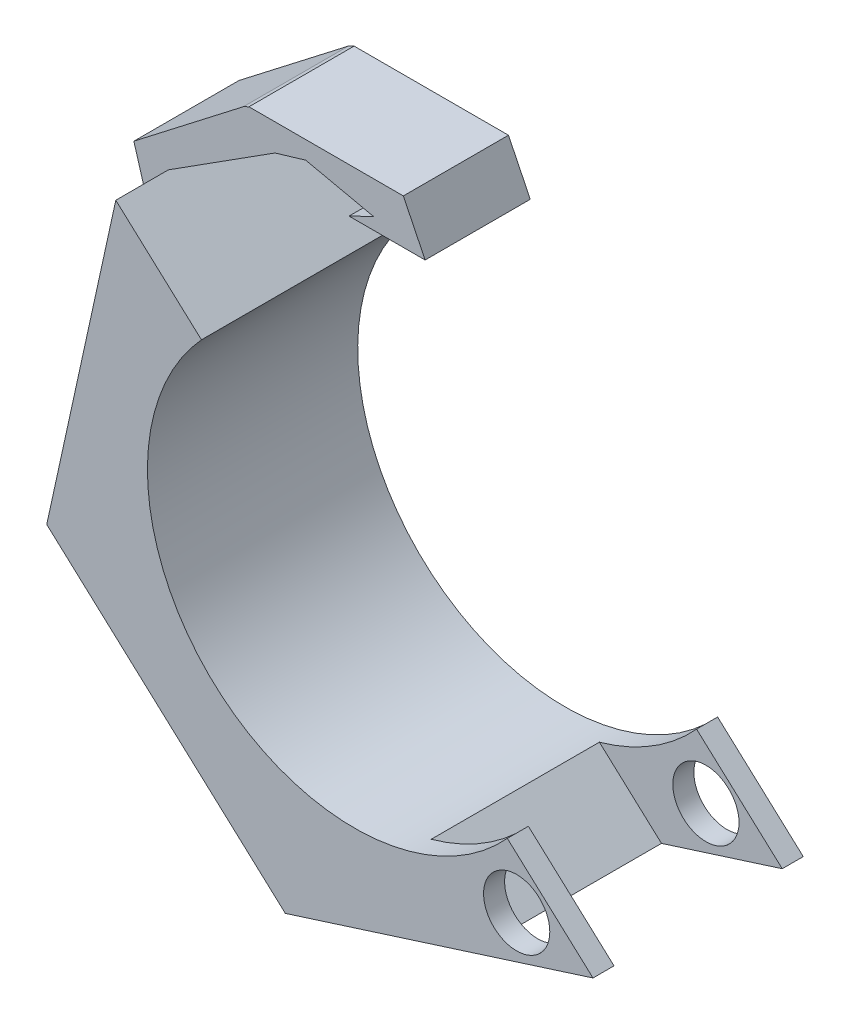
SolidWorks part; units mm, degrees
ref_plane "Front Plane" through (0, 0, 0) normal (0, 0, 1) x (1, 0, 0)
ref_plane "Top Plane" through (0, 0, 0) normal (0, 1, 0) x (1, 0, 0)
ref_plane "Right Plane" through (0, 0, 0) normal (1, 0, 0) x (0, 0, -1)
sketch "Sketch1" plane through (0, 0, 0) normal (0, 0, 1) x (1, 0, 0)
  line L0 (-28.8221, 26.2733) -> (28.8221, -26.2733)
  line L4 (-28.8221, 26.2733) -> (-37.1644, -11.8241)
  line L5 (-37.1644, -11.8241) -> (-8.3422, -38.0973)
  line L6 (-8.3422, -38.0973) -> (28.8221, -26.2733)
  line L8 (32.9933, -7.2246) -> (37.1644, 11.8241) [skipped]
  line L9 (37.1644, 11.8241) -> (8.3422, 38.0973) [skipped]
  line L10 (-10.24, 32.1853) -> (-28.8221, 26.2733) [skipped]
  arc A0 (-18.4757, 16.8418) -> (18.4757, -16.8418) centre (0, 0) ccw
  dimension "D1" = 50
  dimension "D2" = 14
extrude "Boss-Extrude1" add sketch "Sketch1" along normal mid plane 25.4 contours A0 L0 L4 L5 L6
sketch "Sketch2" plane through (0, 0, 0) normal (0, 0, 1) x (1, 0, 0)
  line L0 (3.0458, -20.7137) -> (17.3494, -33.7524)
  line L1 (17.3494, -33.7524) -> (38.9112, -25.4911)
  line L2 (38.9112, -25.4911) -> (19.2495, -2.938)
  line L3 (19.2495, -2.938) -> (3.0458, -20.7137)
  line L4 (18.4757, -16.8418) -> (28.8221, -26.2733) construction
extrude "Cut-Extrude1" cut sketch "Sketch2" against normal mid plane 20.32
sketch "Sketch3" plane through (0, 0, 12.7) normal (0, 0, 1) x (1, 0, 0)
  circle A0 centre (19.6039, -24.0504) radius 4
  dimension "D1" = 8
extrude "Cut-Extrude2" cut sketch "Sketch3" against normal through all both and the other way through all contours A0
sketch "Sketch5" plane through (0, 0, 0) normal (0, 0, 1) x (1, 0, 0)
  line L12 (-30.4779, 18.7117) -> (-32.9933, 27.1866)
  line L14 (-28.8221, 26.2733) -> (-37.1644, -11.8241) construction
  line L15 (-32.9933, 27.1866) -> (-19.7567, 37.4119)
  line L16 (-19.7567, 37.4119) -> (-19.0863, 37.7394)
  line L17 (-19.0863, 37.7394) -> (-0.4379, 37.7394)
  line L18 (-0.4379, 37.7394) -> (2.1951, 32.3479)
  line L19 (2.1951, 32.3479) -> (-6.9966, 32.3479)
  line L20 (-6.9966, 32.3479) -> (-4.0461, 33.7889)
  line L21 (-4.0461, 33.7889) -> (-12.2295, 35.5808)
  line L22 (-12.2295, 35.5808) -> (-15.9398, 34.4796)
  line L23 (-15.9398, 34.4796) -> (-28.8221, 26.2733)
  line L24 (-28.8221, 26.2733) -> (-30.4779, 18.7117)
  point P4 (-1.3278, 30.6637)
  dimension "D1" = 6
extrude "Boss-Extrude2" add sketch "Sketch5" along normal mid plane 12.7
